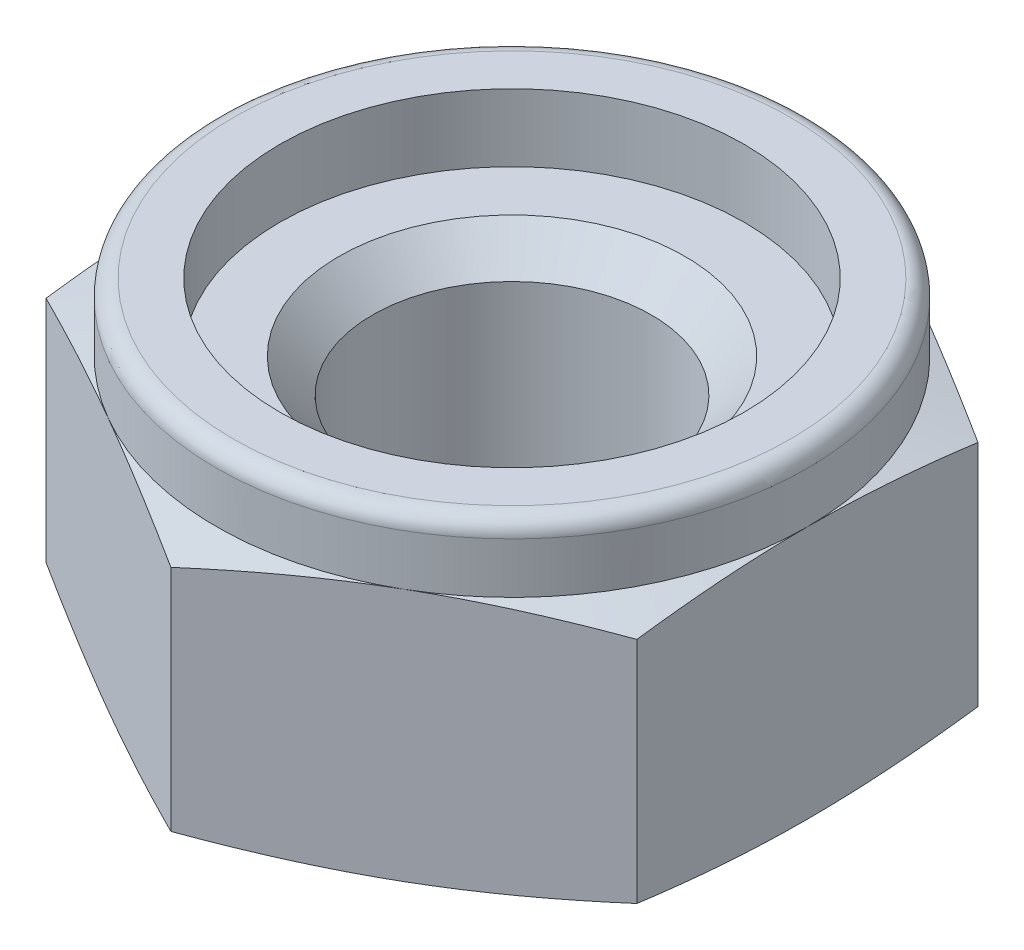
SolidWorks part; units mm, degrees
ref_plane "Front Plane" through (0, 0, 0) normal (0, 0, 1) x (1, 0, 0)
ref_plane "Top Plane" through (0, 0, 0) normal (0, 1, 0) x (1, 0, 0)
ref_plane "Right Plane" through (0, 0, 0) normal (1, 0, 0) x (0, 0, -1)
sketch "Sketch1" plane through (0, 0, 0) normal (0, 1, 0) x (1, 0, 0)
  line L1 (0, 4.0415) -> (-3.5, 2.0207)
  line L2 (-3.5, 2.0207) -> (-3.5, -2.0207)
  line L3 (-3.5, -2.0207) -> (0, -4.0415)
  line L4 (0, -4.0415) -> (3.5, -2.0207)
  line L5 (3.5, -2.0207) -> (3.5, 2.0207)
  line L6 (3.5, 2.0207) -> (0, 4.0415)
  circle A0 centre (0, 0) radius 3.5 construction
  dimension "UNT_S" = 7
extrude "Boss-Extrude1" add sketch "Sketch1" against normal blind 3
sketch "Sketch2" plane through (0, 0, 0) normal (1, 0, 0) x (0, 0, -1)
  line L0 (0, 0) -> (0, -3) construction
  line L1 (-2.0207, -3) -> (2.0207, -3) construction
  line L2 (3.5, 0) -> (4.0415, 0)
  line L3 (4.0415, 0) -> (4.0415, -0.1451)
  line L4 (4.0415, -0.1451) -> (3.5, 0)
  line L5 (2.0207, 0) -> (4.0415, 0) construction
  line L6 (4.0415, -3) -> (4.0415, 0) construction
  line L7 (2.0207, -3) -> (4.0415, -3) construction
  line L8 (4.0415, -2.8549) -> (3.5, -3)
  line L9 (4.0415, -3) -> (4.0415, -2.8549)
  line L10 (3.5, -3) -> (4.0415, -3)
  dimension "D1" = 15
revolve "Cut-Revolve1" cut sketch "Sketch2" angle 360 about L0
hole_wizard "Tapped Hole1" positions "Sketch4" profile "Sketch3" tap size "M4x0.7" standard "JIS" end condition through all
sketch "Sketch4" plane through (0, 0, 0) normal (0, 1, 0) x (1, 0, 0)
  point P0 (0, 0)
sketch "Sketch3" plane through (0, 0, 0) normal (1, 0, 0) x (0, 0, 1)
  line L0 (0, 0) -> (0, 3)
  line L1 (0, 3) -> (1.65, 3)
  line L2 (1.65, 3) -> (1.65, 0)
  line L5 (1.65, 0) -> (0, 0)
  line L11 (0, 0) -> (0, 3) construction
  dimension "Thru Tap Drill Dia." = 3.3
  dimension "Thru Tap Drill Depth" = 3
cosmetic thread "Hole Thread1" parameters "UNT_M"=4
chamfer "Chamfer1" distance 0.4 angle 45 2 edges at (0, -3, 1.65) (0, 0, 1.65)
sketch "Sketch5" plane through (0, 0, 0) normal (0, 0, 1) x (1, 0, 0)
  line L0 (3.5, 0) -> (3.5, 0.8)
  line L1 (3.5, 0.8) -> (2.75, 0.8)
  line L3 (3.5, 0) -> (2.75, 0)
  line L4 (-1.75, -3) -> (1.75, -3) construction
  line L5 (2.75, 0.8) -> (2.75, 0)
  line L6 (3.5, -2.8549) -> (3.5, -0.1451) construction
  line L8 (1.75, 0) -> (-1.75, 0) construction
  line L9 (0, 0) -> (0, 0.8) construction
  dimension "UNT_H_s" = 3.8
  dimension "UNT_MSM_1" = 5.5
revolve "Revolve1" add sketch "Sketch5" angle 360 about L9
fillet "Fillet1" radius 0.2 1 edges at (0, 0.8, -3.5)
